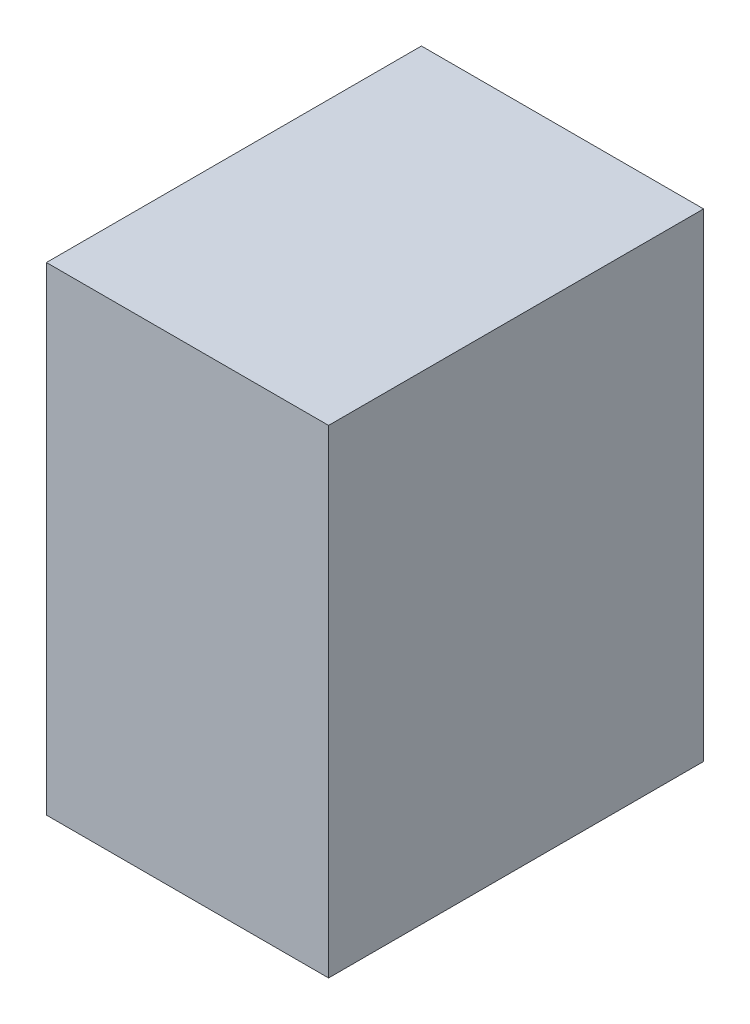
SolidWorks part; units mm, degrees
ref_plane "Front Plane" through (0, 0, 0) normal (0, 0, 1) x (1, 0, 0)
ref_plane "Top Plane" through (0, 0, 0) normal (0, 1, 0) x (1, 0, 0)
ref_plane "Right Plane" through (0, 0, 0) normal (1, 0, 0) x (0, 0, -1)
sketch "Sketch1" plane through (0, 0, 0) normal (0, 0, 1) x (1, 0, 0)
  line L0 (-0.3762, 0.6762) -> (0.3762, 0.6762)
  line L1 (0.3762, 0.6762) -> (0.3762, -0.6)
  line L2 (0.3762, -0.6) -> (-0.3762, -0.6)
  line L3 (-0.3762, -0.6) -> (-0.3762, 0.6762)
extrude "Component_Outline" add sketch "Sketch1" along normal blind 1 separate body
sketch3d "3DSketch1"
  line L0 (0, 0, 0) -> (1, 0, 0)
  line L1 (0, 0, 0) -> (0, 1, 0)
  line L2 (0, 0, 0) -> (0, 0, 1)
  point P0 (0, 0, 0)
